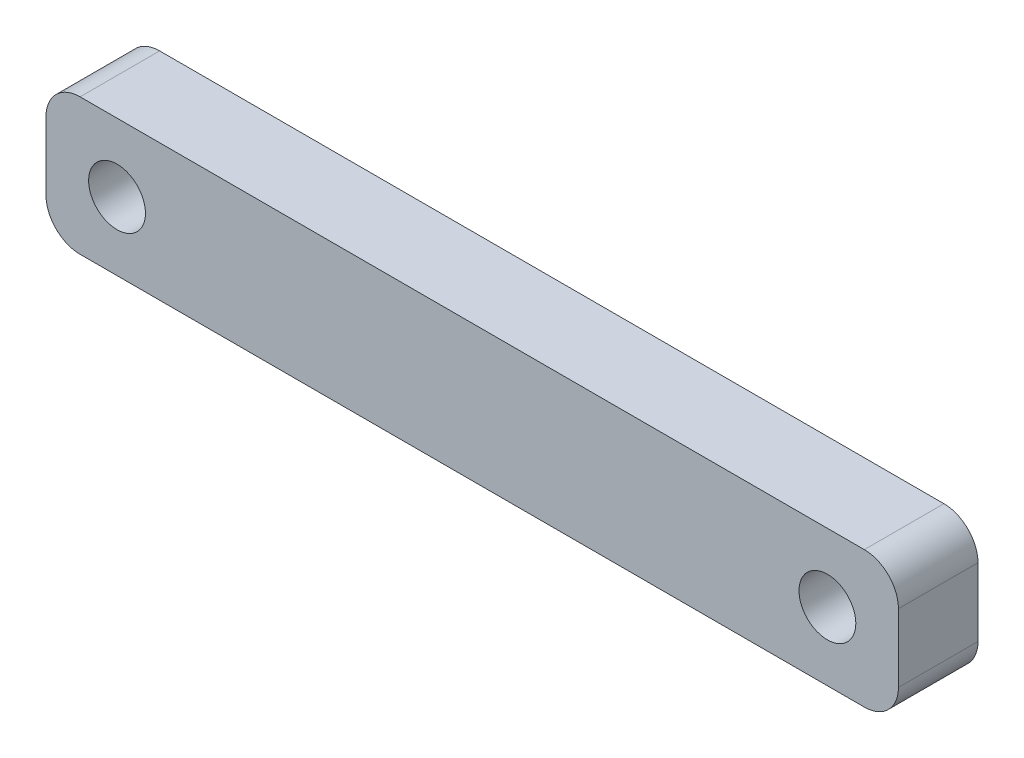
SolidWorks part; units mm, degrees
ref_plane "Front Plane" through (0, 0, 0) normal (0, 0, 1) x (1, 0, 0)
ref_plane "Top Plane" through (0, 0, 0) normal (0, 1, 0) x (1, 0, 0)
ref_plane "Right Plane" through (0, 0, 0) normal (1, 0, 0) x (0, 0, -1)
sketch "Sketch1" plane through (0, 0, 0) normal (0, 0, 1) x (1, 0, 0)
  line L0 (-37.5, 0) -> (37.5, 0) construction
  line L1 (-37.5, -6) -> (37.5, -6)
  line L2 (-37.5, -6) -> (-37.5, 6)
  line L3 (-37.5, 6) -> (37.5, 6)
  line L4 (37.5, -6) -> (37.5, 6)
  line L5 (-37.5, -6) -> (37.5, 6) construction
  line L6 (-37.5, 6) -> (37.5, -6) construction
  line L7 (0, -15.0457) -> (0, 18.7604) construction
  circle A0 centre (31.25, 0) radius 2.5
  circle A1 centre (-31.25, 0) radius 2.5
  point P0 (0, 0)
  point P14 (0, 0)
  dimension "D2" = 5
  dimension "D3" = 5
  dimension "D1" = 75
  dimension "D4" = 12
  dimension "D5" = 62.5
extrude "Boss-Extrude1" add sketch "Sketch1" along normal blind 7
fillet "Fillet1" radius 3 4 edges at (-37.5, -6, 3.5) (-37.5, 6, 3.5) (37.5, -6, 3.5) (37.5, 6, 3.5)
